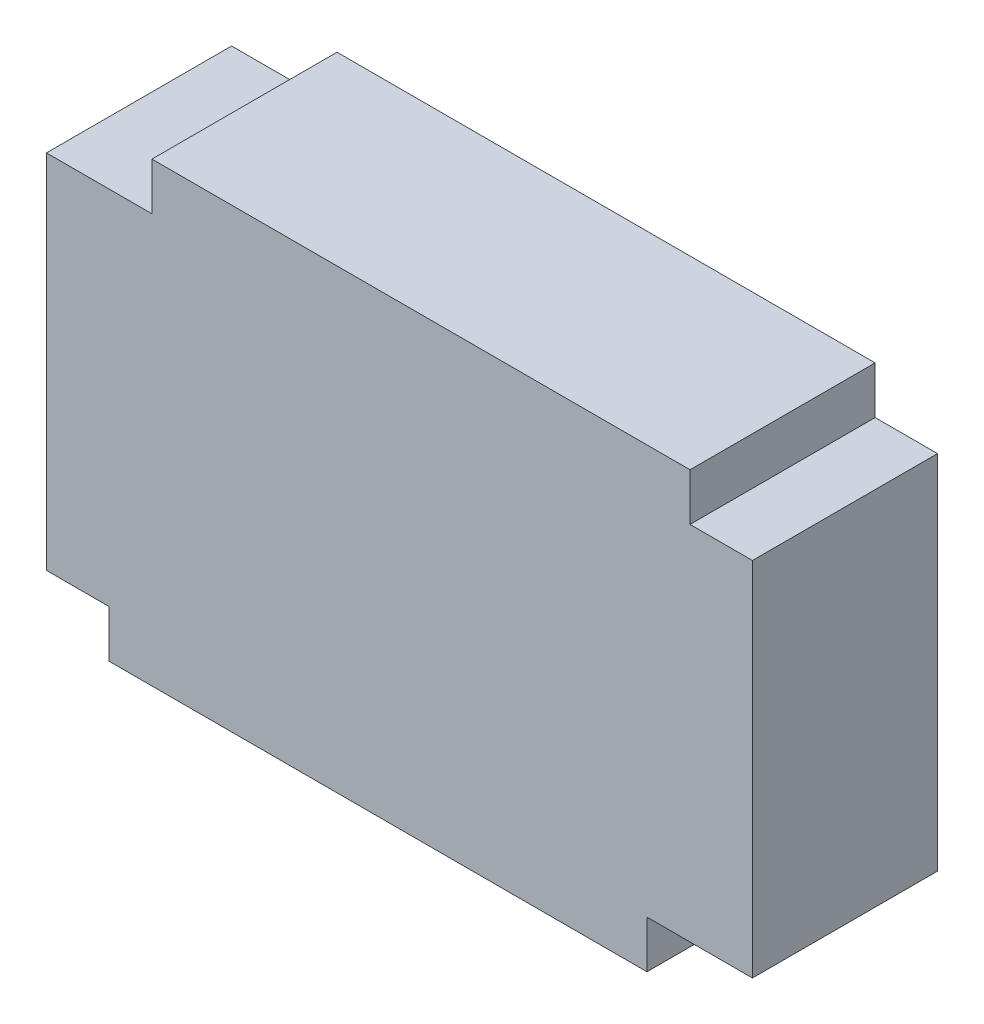
SolidWorks part; units mm, degrees
ref_plane "前视基准面" through (0, 0, 0) normal (0, 0, 1) x (1, 0, 0)
ref_plane "上视基准面" through (0, 0, 0) normal (0, 1, 0) x (1, 0, 0)
ref_plane "右视基准面" through (0, 0, 0) normal (1, 0, 0) x (0, 0, -1)
sketch "草图1" plane through (0, 0, 0) normal (0, 0, 1) x (1, 0, 0)
  line L0 (2.875, -2.65) -> (2.875, -2.1)
  line L1 (2.875, -2.1) -> (4.1, -2.1)
  line L2 (4.1, -2.1) -> (4.1, 2.1)
  line L3 (4.1, 2.1) -> (3.375, 2.1)
  line L4 (3.375, 2.1) -> (3.375, 2.65)
  line L5 (3.375, 2.65) -> (-2.875, 2.65)
  line L6 (-2.875, 2.65) -> (-2.875, 2.1)
  line L7 (-2.875, 2.1) -> (-4.1, 2.1)
  line L8 (-4.1, 2.1) -> (-4.1, -2.1)
  line L9 (-4.1, -2.1) -> (-3.375, -2.1)
  line L10 (-3.375, -2.1) -> (-3.375, -2.65)
  line L11 (-3.375, -2.65) -> (2.875, -2.65)
extrude "Component_Outline" add sketch "草图1" along normal blind 2.15 separate body
sketch3d "3D草图1"
  line L0 (0, 0, 0) -> (1, 0, 0)
  line L1 (0, 0, 0) -> (0, 1, 0)
  line L2 (0, 0, 0) -> (0, 0, 1)
  point P0 (0, 0, 0)
